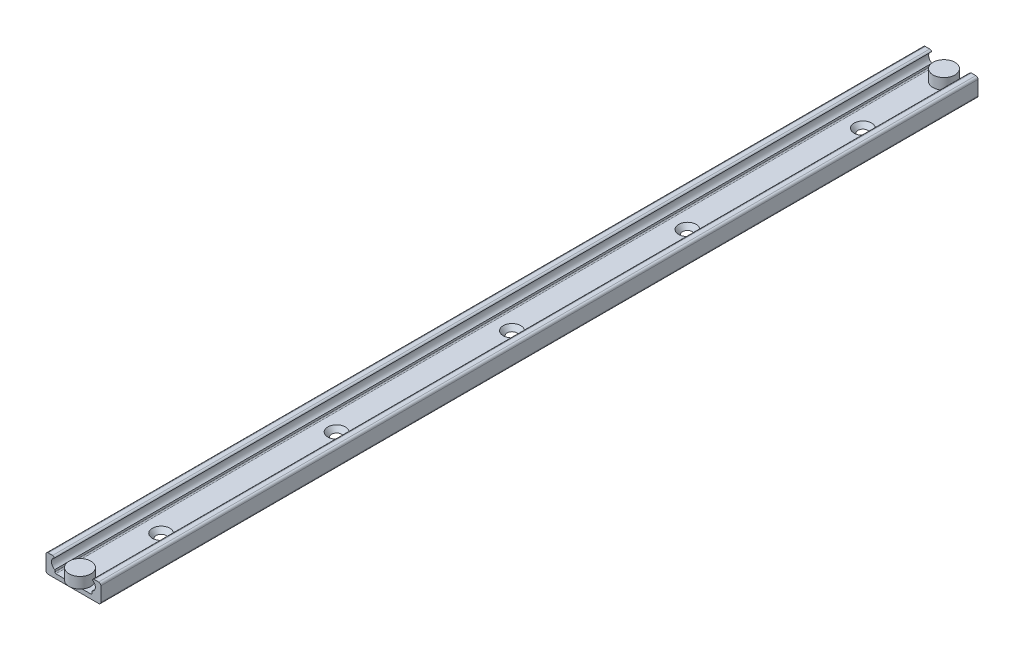
SolidWorks part; units mm, degrees
ref_plane "Front Plane" through (0, 0, 0) normal (0, 0, 1) x (1, 0, 0)
ref_plane "Top Plane" through (0, 0, 0) normal (0, 1, 0) x (1, 0, 0)
ref_plane "Right Plane" through (0, 0, 0) normal (1, 0, 0) x (0, 0, -1)
ref_plane "Plane1" through (0, 0, 0) normal (0, 0, 1) x (1, 0, 0)
sketch "Sketch1" plane through (0, 0, 0) normal (0, 0, 1) x (1, 0, 0)
  line L0 (-11.5, 0) -> (11.5, 0)
  line L1 (12.5, 1) -> (12.5, 7.5)
  line L2 (11.5, 8.5) -> (9.5, 8.5)
  line L3 (8.5, 3.4087) -> (8.5, 2.5)
  line L4 (8, 2) -> (-8, 2)
  line L5 (-8.5, 2.5) -> (-8.5, 3.4087)
  line L6 (-9.5, 8.5) -> (-11.5, 8.5)
  line L7 (-12.5, 7.5) -> (-12.5, 1)
  arc A0 (-12.5, 1) -> (-11.5, 0) centre (-11.5, 1) ccw
  arc A1 (11.5, 0) -> (12.5, 1) centre (11.5, 1) ccw
  arc A2 (12.5, 7.5) -> (11.5, 8.5) centre (11.5, 7.5) ccw
  arc A3 (9.5, 8.5) -> (8.6036, 7.9432) centre (9.5, 7.5) ccw
  arc A4 (8.6036, 7.9432) -> (8.5, 3.4087) centre (7.5, 5.7) cw
  arc A5 (8.5, 2.5) -> (8, 2) centre (8, 2.5) cw
  arc A6 (-8, 2) -> (-8.5, 2.5) centre (-8, 2.5) cw
  arc A7 (-8.5, 3.4087) -> (-8.6036, 7.9432) centre (-7.5, 5.7) cw
  arc A8 (-8.6036, 7.9432) -> (-9.5, 8.5) centre (-9.5, 7.5) ccw
  arc A9 (-11.5, 8.5) -> (-12.5, 7.5) centre (-11.5, 7.5) ccw
extrude "Boss-Extrude1" add sketch "Sketch1" along normal blind 400
ref_plane "Plane2" through (0, 0, 40) normal (0, 0, 1) x (1, 0, 0)
sketch "Sketch2" plane through (0, 0, 40) normal (0, 0, 1) x (1, 0, 0)
  line L0 (0, 2) -> (4, 2)
  line L1 (4, 2) -> (2.25, 0)
  line L2 (2.25, 0) -> (0, 0)
  line L3 (0, 0) -> (0, 2)
  line L4 (0, 0) -> (0, 2) construction
revolve "Cut-Revolve1" cut sketch "Sketch2" angle 360 about L4
ref_plane "Plane3" through (0, 0, 120) normal (0, 0, 1) x (1, 0, 0)
sketch "Sketch3" plane through (0, 0, 120) normal (0, 0, 1) x (1, 0, 0)
  line L0 (0, 2) -> (4, 2)
  line L1 (4, 2) -> (2.25, 0)
  line L2 (2.25, 0) -> (0, 0)
  line L3 (0, 0) -> (0, 2)
  line L4 (0, 0) -> (0, 2) construction
revolve "Cut-Revolve2" cut sketch "Sketch3" angle 360 about L4
ref_plane "Plane4" through (0, 0, 200) normal (0, 0, 1) x (1, 0, 0)
sketch "Sketch4" plane through (0, 0, 200) normal (0, 0, 1) x (1, 0, 0)
  line L0 (0, 2) -> (4, 2)
  line L1 (4, 2) -> (2.25, 0)
  line L2 (2.25, 0) -> (0, 0)
  line L3 (0, 0) -> (0, 2)
  line L4 (0, 0) -> (0, 2) construction
revolve "Cut-Revolve3" cut sketch "Sketch4" angle 360 about L4
ref_plane "Plane5" through (0, 0, 280) normal (0, 0, 1) x (1, 0, 0)
sketch "Sketch5" plane through (0, 0, 280) normal (0, 0, 1) x (1, 0, 0)
  line L0 (0, 2) -> (4, 2)
  line L1 (4, 2) -> (2.25, 0)
  line L2 (2.25, 0) -> (0, 0)
  line L3 (0, 0) -> (0, 2)
  line L4 (0, 0) -> (0, 2) construction
revolve "Cut-Revolve4" cut sketch "Sketch5" angle 360 about L4
ref_plane "Plane6" through (0, 0, 360) normal (0, 0, 1) x (1, 0, 0)
sketch "Sketch6" plane through (0, 0, 360) normal (0, 0, 1) x (1, 0, 0)
  line L0 (0, 2) -> (4, 2)
  line L1 (4, 2) -> (2.25, 0)
  line L2 (2.25, 0) -> (0, 0)
  line L3 (0, 0) -> (0, 2)
  line L4 (0, 0) -> (0, 2) construction
revolve "Cut-Revolve5" cut sketch "Sketch6" angle 360 about L4
ref_plane "Plane7" through (0, 2, 0) normal (0, 1, 0) x (1, 0, 0)
sketch "Sketch7" plane through (0, 2, 0) normal (0, 1, 0) x (1, 0, 0)
  circle A0 centre (0, -3) radius 5
extrude "Boss-Extrude2" add sketch "Sketch7" along normal blind 5
ref_plane "Plane8" through (0, 2, 0) normal (0, 1, 0) x (1, 0, 0)
sketch "Sketch8" plane through (0, 2, 0) normal (0, 1, 0) x (1, 0, 0)
  circle A0 centre (0, -397) radius 5
extrude "Boss-Extrude3" add sketch "Sketch8" along normal blind 5
